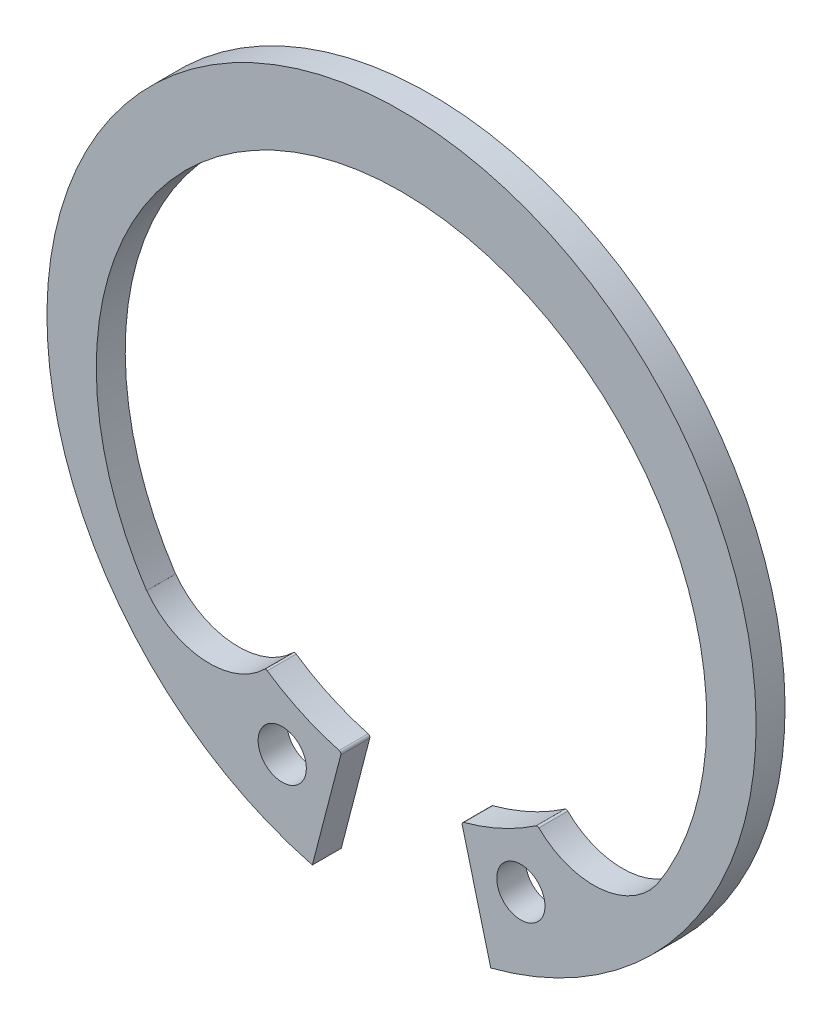
SolidWorks part; units mm, degrees
ref_plane "Plane1" through (0, 0, 0) normal (0, 0, 1) x (1, 0, 0)
ref_plane "Plane2" through (0, 0, 0) normal (0, 1, 0) x (1, 0, 0)
ref_plane "Plane3" through (0, 0, 0) normal (1, 0, 0) x (0, 0, -1)
sketch "Clipboard" plane through (0, 0, 0) normal (0, 0, 1) x (1, 0, 0)
  line L0 (0, 0) -> (2.9, 0)
  line L1 (0, 0) -> (0, 1.45)
  line L2 (0, 0) -> (0, -4.8)
  circle A0 centre (0, 0) radius 1
  circle A1 centre (0, 0) radius 14
  dimension "HoleDia" = 2
  dimension "BoreDia" = 28
  dimension "LargeSection" = 2.9
  dimension "SmallSection" = 1.45
  dimension "LugSection" = 4.8
sketch "BodySke" plane through (0, 0, 0) normal (0, 0, 1) x (1, 0, 0)
  line L0 (-1.5431, 0) -> (1.5431, 0) construction
  line L1 (0, 0) -> (0, 11.8) construction
  line L2 (3.6983, -14.2272) -> (2.9619, -11.3942)
  line L3 (-3.6983, -14.2272) -> (-2.9619, -11.3942)
  line L4 (0, 0) -> (10.306, -10.4822) construction
  line L5 (0, 0) -> (-10.306, -10.4822) construction
  line L6 (-4.6944, -9.9106) -> (-5.1975, -11.8463) construction
  line L7 (4.7571, -10.152) -> (5.1348, -11.6049) construction
  arc A0 (-2.9619, -11.3942) -> (-6.3981, -9.4314) centre (-4.946, -10.8784) ccw
  arc A1 (6.3981, -9.4314) -> (2.9619, -11.3942) centre (4.946, -10.8784) ccw
  arc A2 (9.2894, -9.4482) -> (-9.2894, -9.4482) centre (0, -0.8547) ccw construction
  arc A3 (3.6983, -14.2272) -> (-3.6983, -14.2272) centre (0, 0) ccw
  circle A4 centre (4.946, -10.8784) radius 1
  circle A5 centre (-4.946, -10.8784) radius 1
  circle A6 centre (4.946, -10.8784) radius 2.05 construction
  arc A7 (9.3678, -9.3627) -> (-9.3678, -9.3627) centre (0, -0.8547) ccw
  arc A8 (-4.946, -10.8784) -> (4.946, -10.8784) centre (0, 0) ccw construction
  arc A9 (-9.3678, -9.3627) -> (-6.3981, -9.4314) centre (-7.8503, -7.9845) ccw
  arc A10 (6.3981, -9.4314) -> (9.3678, -9.3627) centre (7.8503, -7.9845) ccw
  dimension "GrooveDia" = 29.4
  dimension "TipRad" = 2.05
  dimension "HoleOffsetRad" = 11.95
  dimension "HoleDia" = 2
  dimension "FilletRad" = 2.05
  dimension "LargeRad" = 11.8
  dimension "SmallRad" = 13.25
  dimension "SmallAngle" = 89.029
  dimension "GapAngle" = 29.143
extrude "Body" add sketch "BodySke" against normal blind 1.2
sketch "ModLugSke" plane through (0, 0, 0) normal (0, 0, 1) x (1, 0, 0)
  line L0 (3.6983, -14.2272) -> (2.5157, -9.6779)
  line L1 (-3.6983, -14.2272) -> (-2.5157, -9.6779)
  line L2 (7.9601, -5.8862) -> (11.8195, -8.74) construction
  line L3 (-7.9601, -5.8862) -> (-11.8195, -8.74) construction
  line L4 (-3.6983, -14.2272) -> (-2.9619, -11.3942) construction
  line L5 (2.9619, -11.3942) -> (3.6983, -14.2272) construction
  line L6 (0, 0) -> (0, -18.0732) construction
  line L7 (10.5634, -7.8112) -> (11.8195, -8.74)
  line L8 (-11.8195, -8.74) -> (-10.5634, -7.8112)
  arc A0 (3.6983, -14.2272) -> (11.8195, -8.74) centre (0, 0) ccw
  arc A1 (-5.5669, -8.1866) -> (-2.5864, -9.5562) centre (0, 0) ccw
  arc A2 (3.6983, -14.2272) -> (-3.6983, -14.2272) centre (0, 0) ccw construction
  arc A3 (6.3981, -9.4314) -> (2.9619, -11.3942) centre (4.946, -10.8784) ccw construction
  arc A4 (-5.5669, -8.1866) -> (-5.6931, -8.1979) centre (-5.6231, -8.2693) ccw
  arc A5 (-10.5634, -7.8112) -> (-5.6931, -8.1979) centre (-7.9601, -5.8862) ccw
  arc A6 (9.3678, -9.3627) -> (-9.3678, -9.3627) centre (0, -0.8547) ccw construction
  arc A7 (5.6931, -8.1979) -> (10.5634, -7.8112) centre (7.9601, -5.8862) ccw
  arc A8 (2.5864, -9.5562) -> (5.5669, -8.1866) centre (0, 0) ccw
  arc A9 (-11.8195, -8.74) -> (-3.6983, -14.2272) centre (0, 0) ccw
  circle A10 centre (-4.946, -10.8784) radius 1
  circle A11 centre (-4.946, -10.8784) radius 1 construction
  circle A12 centre (4.946, -10.8784) radius 1
  circle A13 centre (4.946, -10.8784) radius 1 construction
  arc A14 (-2.5864, -9.5562) -> (-2.5157, -9.6779) centre (-2.6125, -9.6527) cw
  arc A15 (2.5864, -9.5562) -> (2.5157, -9.6779) centre (2.6125, -9.6527) ccw
  arc A16 (5.5669, -8.1866) -> (5.6931, -8.1979) centre (5.6231, -8.2693) cw
  point P43 (2.4907, -9.5816)
  dimension "D1" = 0.1
  dimension "LugAng" = 68.431
extrude "ModLug" add sketch "ModLugSke" against normal through all
sketch "UnlSke" [suppressed] plane through (0, 0, 0) normal (0, 0, 1) x (1, 0, 0)
  line L0 (2.1178, -8.3352) -> (3.2259, -12.6966)
  line L1 (-2.1178, -8.3352) -> (-3.2259, -12.6966)
  line L2 (-3.2259, -12.6966) -> (-2.1422, -8.4315) construction
  line L3 (2.1422, -8.4315) -> (3.2259, -12.6966) construction
  arc A0 (2.1178, -8.3352) -> (-2.1178, -8.3352) centre (0, 0) ccw
  arc A1 (3.2259, -12.6966) -> (-3.2259, -12.6966) centre (0, 0) ccw
  arc A2 (3.2259, -12.6966) -> (-3.2259, -12.6966) centre (0, 0) ccw construction
  circle A4 centre (-4.4431, -9.5688) radius 1
  circle A5 centre (4.4431, -9.5688) radius 1
  circle A6 centre (4.4431, -9.5688) radius 1 construction
  circle A7 centre (-4.4431, -9.5688) radius 1 construction
  arc A8 (2.2134, -8.3103) -> (4.9183, -7.0548) centre (0, 0) ccw construction
extrude "Unlug" [suppressed] add sketch "UnlSke" against normal through all
equation "' \"BoreDia@Clipboard\" = 8"
equation "' \"Thickness@Body\" = 0.8"
equation "' \"GrooveDia@BodySke\" = 8.4"
equation "' \"LugSection@Clipboard\" = 2.4"
equation "' \"LargeSection@Clipboard\" = 1.1"
equation "' \"HoleDia@Clipboard\" = 1.0"
equation "' \"BoreDia@Clipboard\" = 25"
equation "' \"Thickness@Body\" = 1.2"
equation "' \"GrooveDia@BodySke\" = 26.2"
equation "' \"LugSection@Clipboard\" = 4.5"
equation "' \"LargeSection@Clipboard\" = 2.7"
equation "' \"HoleDia@Clipboard\" = 2"
equation "\"SmallSection@Clipboard\" = \"LargeSection@Clipboard\" * 0.5"
equation "\"TipRad@BodySke\" = (\"LugSection@Clipboard\" - (\"GrooveDia@BodySke\" / 2  -  \"BoreDia@Clipboard\" / 2 ) ) / 2"
equation "\"HoleOffsetRad@BodySke\" = (\"GrooveDia@BodySke\" / 2) - \"LugSection@Clipboard\"  + \"TipRad@BodySke\""
equation "\"LargeRad@BodySke\" =  \"GrooveDia@BodySke\" / 2 -  \"LargeSection@Clipboard\""
equation "\"SmallRad@BodySke\" =  \"GrooveDia@BodySke\" / 2 -  \"SmallSection@Clipboard\""
equation "\"HoleDia@BodySke\" =  \"HoleDia@Clipboard\""
equation "\"FilletRad@BodySke\" = \"TipRad@BodySke\" * 1.0"
equation "\"GapAngle@BodySke\" = 360 - 0.965 * 360 * ( \"BoreDia@Clipboard\" /  \"GrooveDia@BodySke\")"
equation "\"LugAng@ModLugSke\" = \"GapAngle@BodySke\"  + 2 * 360 * (\"LugSection@Clipboard\" / (\"BoreDia@Clipboard\" * 3.1416))"
